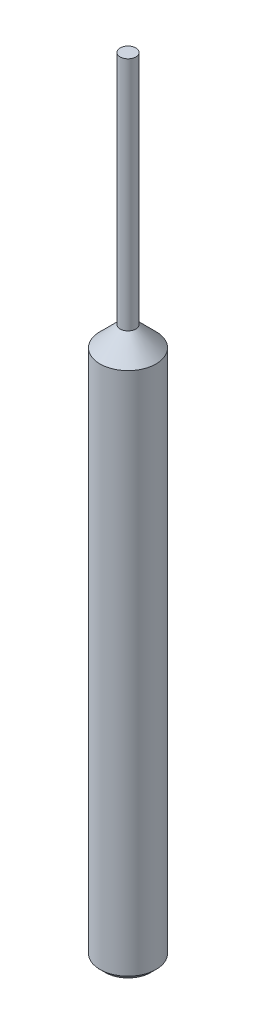
SolidWorks part; units mm, degrees
material "Stahl schwarz"
ref_plane "Vorne" through (0, 0, 0) normal (0, 0, 1) x (1, 0, 0)
ref_plane "Oben" through (0, 0, 0) normal (0, 1, 0) x (1, 0, 0)
ref_plane "Rechts" through (0, 0, 0) normal (1, 0, 0) x (0, 0, -1)
sketch "Skizze2" plane through (0, 0, 0) normal (0, 0, 1) x (1, 0, 0)
  line L0 (0, -34.7937) -> (0, 167.3104) construction
  line L1 (0, 0) -> (4.35, 0)
  line L2 (4.35, 0) -> (5.35, 1)
  line L3 (5.35, 1) -> (5.35, 101.15)
  line L4 (5.35, 101.15) -> (1.5, 105)
  line L5 (1.5, 105) -> (1.5, 150)
  line L6 (1.5, 150) -> (0, 150)
  line L7 (0, 150) -> (0, 0)
  dimension "D1" = 45
  dimension "D2" = 3
  dimension "D3" = 10.7
  dimension "D4" = 1
  dimension "D5" = 135
  dimension "D6" = 150
  dimension "D7" = 45
revolve "Rotation1" add sketch "Skizze2" angle 360 about L0
